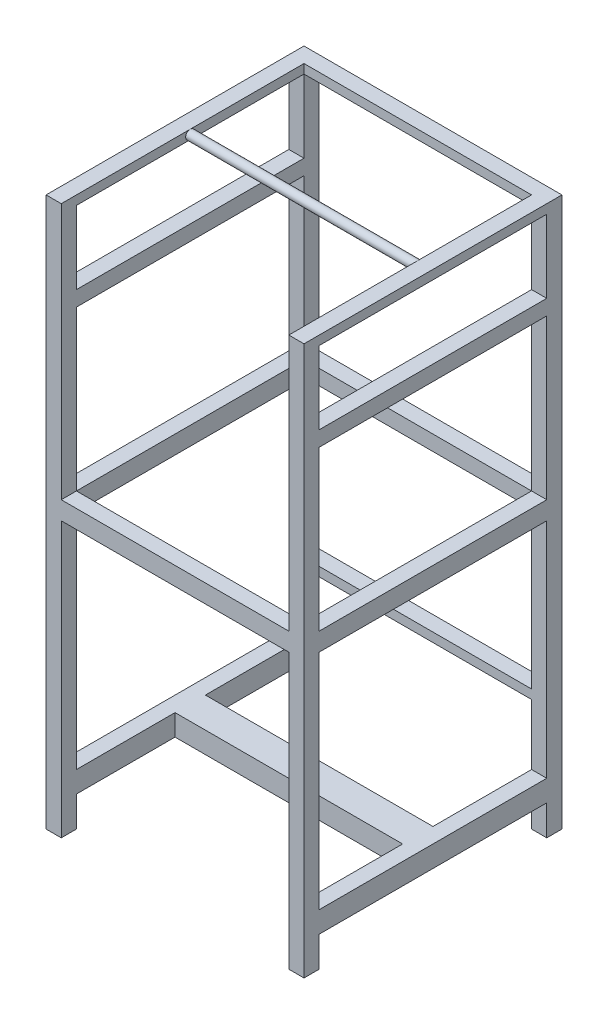
SolidWorks part; units mm, degrees
material "Custom Plastic"
ref_plane "Front Plane" through (0, 0, 0) normal (0, 0, 1) x (1, 0, 0)
ref_plane "Top Plane" through (0, 0, 0) normal (0, 1, 0) x (1, 0, 0)
ref_plane "Right Plane" through (0, 0, 0) normal (1, 0, 0) x (0, 0, -1)
sketch "Sketch1" plane through (0, 0, 0) normal (0, 1, 0) x (1, 0, 0)
  line L1 (-452.7607, 201.6871) -> (397.2393, 201.6871)
  line L2 (-452.7607, 201.6871) -> (-452.7607, -648.3129)
  line L3 (-452.7607, -648.3129) -> (397.2393, -648.3129)
  line L4 (397.2393, 201.6871) -> (397.2393, -648.3129)
  line L5 (-452.7607, 201.6871) -> (-402.7607, 201.6871)
  line L6 (-452.7607, 201.6871) -> (-452.7607, 151.6871)
  line L7 (-452.7607, 151.6871) -> (-402.7607, 151.6871)
  line L8 (-402.7607, 201.6871) -> (-402.7607, 151.6871)
  line L9 (-452.7607, -648.3129) -> (-402.7607, -648.3129)
  line L10 (-452.7607, -648.3129) -> (-452.7607, -598.3129)
  line L11 (-452.7607, -598.3129) -> (-402.7607, -598.3129)
  line L12 (-402.7607, -648.3129) -> (-402.7607, -598.3129)
  line L13 (397.2393, -648.3129) -> (347.2393, -648.3129)
  line L14 (397.2393, -648.3129) -> (397.2393, -598.3129)
  line L15 (397.2393, -598.3129) -> (347.2393, -598.3129)
  line L16 (347.2393, -648.3129) -> (347.2393, -598.3129)
  line L17 (397.2393, 201.6871) -> (347.2393, 201.6871)
  line L18 (397.2393, 201.6871) -> (397.2393, 151.6871)
  line L19 (397.2393, 151.6871) -> (347.2393, 151.6871)
  line L20 (347.2393, 201.6871) -> (347.2393, 151.6871)
  dimension "D1" = 850
  dimension "D2" = 850
  dimension "D3" = 50
  dimension "D4" = 50
  dimension "D5" = 50
  dimension "D6" = 50
  dimension "D7" = 50
  dimension "D8" = 50
  dimension "D9" = 50
  dimension "D10" = 50
extrude "Boss-Extrude1" add sketch "Sketch1" along normal blind 1810 contours L3 L12 L11 L2 | L16 L3 L4 L15 | L1 L20 L19 L4 | L8 L1 L2 L7
sketch "Sketch2" plane through (0, 0, 0) normal (0, -1, 0) x (-1, 0, 0)
  line L1 (452.7607, -598.3129) -> (402.7607, -598.3129)
  line L2 (452.7607, -598.3129) -> (452.7607, 151.6871)
  line L3 (452.7607, 151.6871) -> (402.7607, 151.6871)
  line L4 (402.7607, -598.3129) -> (402.7607, 151.6871)
  line L5 (-347.2393, -598.3129) -> (-397.2393, -598.3129)
  line L6 (-347.2393, -598.3129) -> (-347.2393, 151.6871)
  line L7 (-347.2393, 151.6871) -> (-397.2393, 151.6871)
  line L8 (-397.2393, -598.3129) -> (-397.2393, 151.6871)
  line L9 (402.7607, -273.3129) -> (-347.2393, -273.3129)
  line L10 (402.7607, -273.3129) -> (402.7607, -173.3129)
  line L11 (402.7607, -173.3129) -> (-347.2393, -173.3129)
  line L12 (-347.2393, -273.3129) -> (-347.2393, -173.3129)
  point P16 (402.7607, -223.3129)
  line M4 (402.7607, 151.6871) -> (452.7607, 151.6871)
  dimension "D1" = 100
  dimension "D2" = 50
extrude "Boss-Extrude2" add sketch "Sketch2" against normal blind 180 from offset 10 contours L4 L1 L2 M4 | L4 L11 L6 L9 | L8 L5 L6 L7
sketch "Sketch4" plane through (-452.7607, 0, 0) normal (-1, 0, 0) x (0, 0, 1)
  line L1 (-151.6871, -10) -> (598.3129, -10)
  line L2 (-151.6871, -10) -> (-151.6871, 100)
  line L3 (-151.6871, 100) -> (598.3129, 100)
  line L4 (598.3129, -10) -> (598.3129, 100)
  dimension "D1" = 110
  dimension "D2" = 750
extrude "Cut-Extrude4" cut sketch "Sketch4" against normal blind 1050
sketch "Sketch5" plane through (347.2393, 0, 0) normal (-1, 0, 0) x (0, 0, 1)
  line L0 (-201.6871, 1810) -> (-201.6871, 0) construction
  line L1 (-201.6871, 965) -> (-151.6871, 965)
  line L2 (-201.6871, 965) -> (-201.6871, 915)
  line L3 (-201.6871, 915) -> (-151.6871, 915)
  line L4 (-151.6871, 965) -> (-151.6871, 915)
  line L5 (-151.6871, 1810) -> (-151.6871, 170) construction
  line L6 (-201.6871, 0) -> (-151.6871, 0) construction
  line L7 (598.3129, 1810) -> (598.3129, 170) construction
  line L8 (598.3129, 965) -> (648.3129, 965)
  line L9 (598.3129, 965) -> (598.3129, 905)
  line L10 (598.3129, 905) -> (648.3129, 905)
  line L11 (648.3129, 965) -> (648.3129, 905)
  line L12 (648.3129, 1810) -> (648.3129, 0) construction
  dimension "D1" = 50
  dimension "D2" = 915
extrude "Boss-Extrude3" add sketch "Sketch5" along normal blind 770
sketch "Sketch6" plane through (0, 0, 598.3129) normal (0, 0, -1) x (-1, 0, 0)
  line L0 (-397.2393, 1810) -> (-397.2393, 170) construction
  line L1 (-347.2393, 965) -> (-397.2393, 965)
  line L2 (-347.2393, 965) -> (-347.2393, 905)
  line L3 (-347.2393, 905) -> (-397.2393, 905)
  line L4 (-397.2393, 965) -> (-397.2393, 905)
  line L5 (452.7607, 1810) -> (452.7607, 170) construction
  line L6 (402.7607, 965) -> (452.7607, 965)
  line L7 (402.7607, 965) -> (402.7607, 905)
  line L8 (402.7607, 905) -> (452.7607, 905)
  line L9 (452.7607, 965) -> (452.7607, 905)
  dimension "D1" = 60
extrude "Boss-Extrude4" add sketch "Sketch6" along normal blind 770
sketch "Sketch8" plane through (0, 0, 598.3129) normal (0, 0, -1) x (-1, 0, 0)
  line L0 (-397.2393, 1810) -> (-397.2393, 965) construction
  line L1 (-397.2393, 1539.7401) -> (-347.2393, 1539.7401)
  line L2 (-397.2393, 1539.7401) -> (-397.2393, 1489.7401)
  line L3 (-397.2393, 1489.7401) -> (-347.2393, 1489.7401)
  line L4 (-347.2393, 1539.7401) -> (-347.2393, 1489.7401)
  line L5 (-347.2393, 1810) -> (-347.2393, 965) construction
  line L6 (402.7607, 1810) -> (402.7607, 965) construction
  line L7 (402.7607, 1539.7401) -> (452.7607, 1539.7401)
  line L8 (402.7607, 1539.7401) -> (402.7607, 1489.7401)
  line L9 (402.7607, 1489.7401) -> (452.7607, 1489.7401)
  line L10 (452.7607, 1539.7401) -> (452.7607, 1489.7401)
  line L11 (452.7607, 1810) -> (452.7607, 965) construction
  dimension "D1" = 50
extrude "Boss-Extrude5" add sketch "Sketch8" along normal blind 770
sketch "Sketch9" plane through (0, 0, -151.6871) normal (0, 0, 1) x (1, 0, 0)
  line L0 (-402.7607, 1810) -> (-402.7607, 1539.7401) construction
  line L1 (-452.7607, 1810) -> (-402.7607, 1810)
  line L2 (-452.7607, 1810) -> (-452.7607, 1780)
  line L3 (-452.7607, 1780) -> (-402.7607, 1780)
  line L4 (-402.7607, 1810) -> (-402.7607, 1780)
  line L5 (397.2393, 1810) -> (397.2393, 1539.7401) construction
  line L6 (347.2393, 1810) -> (397.2393, 1810)
  line L7 (347.2393, 1810) -> (347.2393, 1780)
  line L8 (347.2393, 1780) -> (397.2393, 1780)
  line L9 (397.2393, 1810) -> (397.2393, 1780)
  dimension "D1" = 30
  dimension "D2" = 30
extrude "Boss-Extrude6" add sketch "Sketch9" along normal blind 770
sketch "Sketch10" plane through (-402.7607, 0, 0) normal (1, 0, 0) x (0, 0, -1)
  line L0 (-598.3129, 1780) -> (151.6871, 1780) construction
  circle A0 centre (-223.3129, 1795) radius 15
extrude "Boss-Extrude7" add sketch "Sketch10" along normal blind 770
sketch "Sketch11" plane through (347.2393, 0, 0) normal (-1, 0, 0) x (0, 0, 1)
  line L1 (-201.6871, 1810) -> (-151.6871, 1810)
  line L2 (-201.6871, 1810) -> (-201.6871, 1780)
  line L3 (-201.6871, 1780) -> (-151.6871, 1780)
  line L4 (-151.6871, 1810) -> (-151.6871, 1780)
extrude "Boss-Extrude8" add sketch "Sketch11" along normal blind 770
sketch "Sketch12" plane through (347.2393, 0, 0) normal (-1, 0, 0) x (0, 0, 1)
  line L0 (-201.6871, 915) -> (-201.6871, 0) construction
  line L1 (-201.6871, 399.8169) -> (-151.6871, 399.8169)
  line L2 (-201.6871, 399.8169) -> (-201.6871, 369.8169)
  line L3 (-201.6871, 369.8169) -> (-151.6871, 369.8169)
  line L4 (-151.6871, 399.8169) -> (-151.6871, 369.8169)
  line L5 (-151.6871, 905) -> (-151.6871, 170) construction
  dimension "D1" = 30
extrude "Boss-Extrude9" add sketch "Sketch12" along normal blind 770
